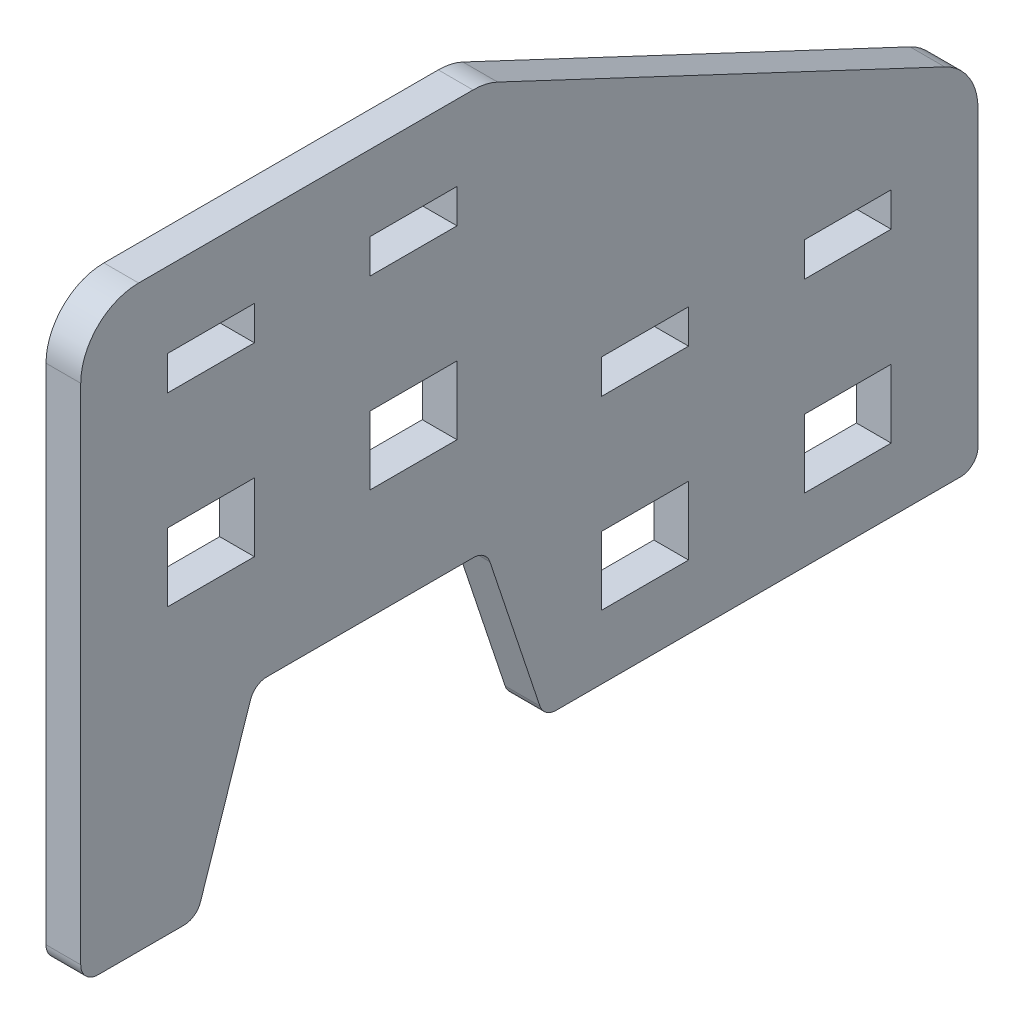
SolidWorks part; units mm, degrees
ref_plane "Front" through (0, 0, 0) normal (0, 0, 1) x (1, 0, 0)
ref_plane "Top" through (0, 0, 0) normal (0, 1, 0) x (1, 0, 0)
ref_plane "Right" through (0, 0, 0) normal (1, 0, 0) x (0, 0, -1)
sketch "Skizze1" plane through (0, 0, 0) normal (1, 0, 0) x (0, 0, -1)
  line L0 (0, 0) -> (20, 0)
  line L1 (20, 0) -> (30, 30)
  line L2 (30, 30) -> (70, 30)
  line L3 (70, 30) -> (80, 0)
  line L4 (80, 0) -> (155, 0)
  line L5 (155, 0) -> (155, 60)
  line L6 (155, 60) -> (70, 100)
  line L7 (70, 100) -> (0, 100)
  line L8 (0, 100) -> (0, 0)
  line L9 (30, 30) -> (20, 30) construction
  line L10 (20, 30) -> (20, 0) construction
  line L11 (70, 30) -> (80, 30) construction
  line L12 (80, 30) -> (80, 0) construction
  dimension "D1" = 100
  dimension "135" = 155
  dimension "D3" = 75
  dimension "D4" = 30
  dimension "D5" = 10
  dimension "D6" = 70
  dimension "D7" = 60
  dimension "D8" = 20
extrude "Grundform" add sketch "Skizze1" along normal blind 6
sketch "Skizze2" plane through (6, 0, 0) normal (1, 0, 0) x (0, 0, -1)
  line L0 (105, 46) -> (125, 46) construction
  line L1 (90, 48.95) -> (105, 48.95)
  line L2 (90, 48.95) -> (90, 43.05)
  line L3 (90, 43.05) -> (105, 43.05)
  line L4 (105, 48.95) -> (105, 43.05)
  line L5 (115, 46) -> (115, 14) construction
  line L6 (115, 30) -> (141.5957, 30) construction
  line L7 (125, 48.95) -> (125, 43.05)
  line L8 (140, 43.05) -> (125, 43.05)
  line L9 (140, 48.95) -> (140, 43.05)
  line L10 (140, 48.95) -> (125, 48.95)
  line L11 (105, 14) -> (125, 14) construction
  line L12 (140, 11.05) -> (125, 11.05)
  line L13 (140, 11.05) -> (140, 16.95)
  line L14 (140, 16.95) -> (125, 16.95)
  line L15 (125, 11.05) -> (125, 16.95)
  line L16 (105, 11.05) -> (105, 16.95)
  line L17 (90, 16.95) -> (105, 16.95)
  line L18 (90, 11.05) -> (90, 16.95)
  line L19 (90, 11.05) -> (105, 11.05)
  line L20 (155, 0) -> (155, 60) construction
  line L21 (80, 0) -> (155, 0) construction
  line L22 (50, 84) -> (40, 84) construction
  line L39 (65, 86.95) -> (65, 81.05)
  line L56 (50, 86.95) -> (50, 81.05)
  line L57 (40, 84) -> (40, 52) construction
  line L58 (40, 68) -> (90.9252, 68) construction
  line L62 (30, 86.95) -> (30, 81.05)
  line L69 (15, 86.95) -> (15, 81.05)
  line L71 (15, 81.05) -> (30, 81.05)
  line L72 (15, 86.95) -> (30, 86.95)
  line L73 (65, 86.95) -> (50, 86.95)
  line L74 (65, 81.05) -> (50, 81.05)
  line L75 (50, 52) -> (40, 52) construction
  line L76 (40, 84) -> (30, 84) construction
  line L80 (15, 49.05) -> (30, 49.05)
  line L81 (15, 49.05) -> (15, 54.95)
  line L82 (15, 54.95) -> (30, 54.95)
  line L83 (30, 49.05) -> (30, 54.95)
  line L84 (50, 49.05) -> (50, 54.95)
  line L85 (65, 54.95) -> (50, 54.95)
  line L86 (65, 49.05) -> (65, 54.95)
  line L87 (65, 49.05) -> (50, 49.05)
  dimension "D1" = 5.9
  dimension "D2" = 15
  dimension "D3" = 20
  dimension "D4" = 32
  dimension "D5" = 40
  dimension "D6" = 30
  dimension "D7" = 75
  dimension "D8" = 38
  dimension "D9" = 20
extrude "Zapfendurchbruch" cut sketch "Skizze2" against normal through all
fillet "Verrundung1" radius 10 3 edges at (3, 100, 0) (3, 100, -70) (3, 60, -155)
fillet "Verrundung2" radius 3 6 edges at (3, 0, 0) (3, 0, -20) (3, 30, -30) (3, 30, -70) (3, 0, -80) (3, 0, -155)
sketch "Skizze3" plane through (0, 0, 0) normal (-1, 0, 0) x (0, 0, 1)
  line L0 (-140, 16.95) -> (-125, 16.95) construction
  line L1 (-140, 16.95) -> (-125, 16.95)
  line L2 (-140, 16.95) -> (-140, 22.85)
  line L3 (-140, 22.85) -> (-125, 22.85)
  line L4 (-125, 16.95) -> (-125, 22.85)
  line L5 (-105, 16.95) -> (-90, 16.95)
  line L6 (-105, 16.95) -> (-105, 22.85)
  line L7 (-105, 22.85) -> (-90, 22.85)
  line L8 (-90, 16.95) -> (-90, 22.85)
  line L9 (-65, 54.95) -> (-50, 54.95)
  line L10 (-65, 54.95) -> (-65, 60.85)
  line L11 (-65, 60.85) -> (-50, 60.85)
  line L12 (-50, 54.95) -> (-50, 60.85)
  line L13 (-30, 54.95) -> (-15, 54.95)
  line L14 (-30, 54.95) -> (-30, 60.85)
  line L15 (-30, 60.85) -> (-15, 60.85)
  line L16 (-15, 54.95) -> (-15, 60.85)
  line L17 (-140, 11.05) -> (-140, 16.95) construction
extrude "Zapfendurchbruch 2" cut sketch "Skizze3" against normal through all
